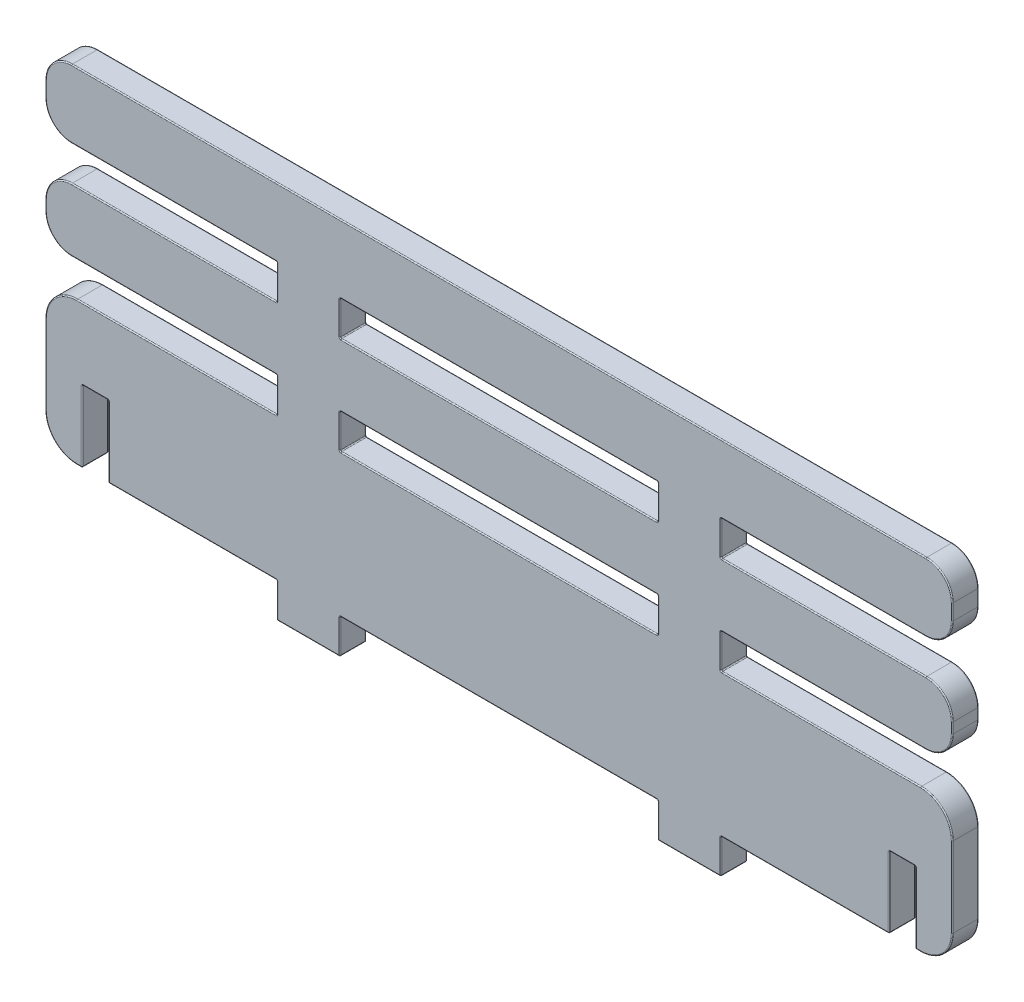
SolidWorks part; units mm, degrees
ref_plane "Plano frontal" through (0, 0, 0) normal (0, 0, 1) x (1, 0, 0)
ref_plane "Plano superior" through (0, 0, 0) normal (0, 1, 0) x (1, 0, 0)
ref_plane "Plano direito" through (0, 0, 0) normal (1, 0, 0) x (0, 0, -1)
sketch "Esboço1" plane through (0, 0, 0) normal (0, 0, 1) x (1, 0, 0)
  line L0 (-195.7976, 69.0191) -> (-116.5976, 69.0191)
  line L1 (-195.7976, 93.1191) -> (-195.7976, 86.3191)
  line L2 (-193.2976, 93.1191) -> (-193.2976, 86.3191)
  line L3 (-199.2976, 72.5188) -> (-199.2976, 119.0191) construction
  line L4 (-193.2976, 76.0191) -> (-195.7976, 76.0191)
  line L5 (-174.2976, 64.0191) -> (-174.2976, 119.0618) construction
  line L6 (-195.7976, 76.0191) -> (-195.7976, 83.0191)
  line L7 (-193.2976, 76.0191) -> (-193.2976, 83.0191)
  line L8 (-116.5976, 76.0191) -> (-116.5976, 83.0191)
  line L9 (-156.1976, 131.9283) -> (-156.1976, 54.9849) construction
  line L10 (-141.0976, 83.0191) -> (-141.0976, 112.5191) construction
  line L11 (-113.0976, 112.5191) -> (-199.2976, 112.5191)
  line L12 (-135.0976, 112.5191) -> (-135.0976, 83.0191) construction
  line L13 (-113.0976, 103.2191) -> (-199.2976, 103.2191)
  line L14 (-138.0976, 64.0191) -> (-138.0976, 119.0618) construction
  line L15 (-116.0976, 86.3191) -> (-196.2976, 86.3191)
  line L16 (-113.0976, 72.5188) -> (-113.0976, 119.0191) construction
  line L17 (-141.0976, 83.0191) -> (-141.0976, 86.3191)
  line L18 (-135.0976, 86.3191) -> (-141.0976, 86.3191)
  line L19 (-135.0976, 83.0191) -> (-135.0976, 86.3191)
  line L20 (-135.0976, 83.0191) -> (-141.0976, 83.0191)
  line L21 (-141.0976, 103.2191) -> (-141.0976, 99.9191)
  line L22 (-135.0976, 99.9191) -> (-141.0976, 99.9191)
  line L23 (-135.0976, 103.2191) -> (-135.0976, 99.9191)
  line L24 (-135.0976, 103.2191) -> (-141.0976, 103.2191)
  line L25 (-141.0976, 112.5191) -> (-141.0976, 109.2191)
  line L26 (-135.0976, 109.2191) -> (-141.0976, 109.2191)
  line L27 (-135.0976, 112.5191) -> (-135.0976, 109.2191)
  line L28 (-135.0976, 112.5191) -> (-141.0976, 112.5191)
  line L29 (-119.0976, 93.1191) -> (-116.5976, 93.1191)
  line L30 (-113.0976, 109.2191) -> (-113.0976, 103.2191)
  line L31 (-113.0976, 119.0191) -> (-113.0976, 112.5191)
  line L32 (-113.0976, 89.3191) -> (-113.0976, 96.9191)
  line L33 (-113.0976, 80.0191) -> (-113.0976, 72.5188)
  line L34 (-119.0976, 76.0191) -> (-119.0976, 83.0191)
  line L36 (-196.2976, 83.0191) -> (-116.0976, 83.0191)
  line L37 (-199.2976, 80.0191) -> (-199.2976, 72.5188)
  line L39 (-119.0976, 76.0191) -> (-116.5976, 76.0191)
  line L40 (-119.0976, 93.1191) -> (-119.0976, 86.3191)
  line L41 (-116.5976, 93.1191) -> (-116.5976, 86.3191)
  line L58 (-199.2976, 119.0191) -> (-113.0976, 119.0191)
  line L61 (-199.2976, 89.3191) -> (-199.2976, 96.9191)
  line L62 (-196.2976, 99.9191) -> (-116.0976, 99.9191)
  line L64 (-199.2976, 109.2191) -> (-113.0976, 109.2191)
  line L66 (-199.2976, 119.0191) -> (-199.2976, 112.5191)
  line L67 (-199.2976, 109.2191) -> (-199.2976, 103.2191)
  line L71 (-177.2976, 112.5191) -> (-177.2976, 83.0191) construction
  line L72 (-193.2976, 93.1191) -> (-195.7976, 93.1191)
  line L76 (-171.2976, 83.0191) -> (-171.2976, 112.5191) construction
  line L80 (-177.2976, 112.5191) -> (-171.2976, 112.5191)
  line L81 (-177.2976, 112.5191) -> (-177.2976, 109.2191)
  line L82 (-177.2976, 109.2191) -> (-171.2976, 109.2191)
  line L83 (-171.2976, 112.5191) -> (-171.2976, 109.2191)
  line L84 (-177.2976, 103.2191) -> (-171.2976, 103.2191)
  line L85 (-177.2976, 103.2191) -> (-177.2976, 99.9191)
  line L86 (-177.2976, 99.9191) -> (-171.2976, 99.9191)
  line L87 (-171.2976, 103.2191) -> (-171.2976, 99.9191)
  line L88 (-177.2976, 83.0191) -> (-171.2976, 83.0191)
  line L89 (-177.2976, 83.0191) -> (-177.2976, 86.3191)
  line L90 (-177.2976, 86.3191) -> (-171.2976, 86.3191)
  line L91 (-171.2976, 83.0191) -> (-171.2976, 86.3191)
  arc A0 (-116.0976, 86.3191) -> (-113.0976, 89.3191) centre (-116.0976, 89.3191) ccw
  arc A1 (-113.0976, 96.9191) -> (-116.0976, 99.9191) centre (-116.0976, 96.9191) ccw
  arc A2 (-116.0976, 83.0191) -> (-113.0976, 80.0191) centre (-116.0976, 80.0191) cw
  arc A3 (-116.5976, 69.0191) -> (-113.0976, 72.5188) centre (-116.5973, 72.5188) ccw
  arc A6 (-195.7976, 69.0191) -> (-199.2976, 72.5188) centre (-195.798, 72.5188) cw
  arc A7 (-196.2976, 83.0191) -> (-199.2976, 80.0191) centre (-196.2976, 80.0191) ccw
  arc A10 (-199.2976, 96.9191) -> (-196.2976, 99.9191) centre (-196.2976, 96.9191) cw
  arc A11 (-196.2976, 86.3191) -> (-199.2976, 89.3191) centre (-196.2976, 89.3191) cw
  point P8 (-156.1976, 83.0191)
  point P10 (-156.1976, 99.9191)
  point P11 (-156.1976, 112.5191)
  point P12 (-156.1976, 119.0191)
  point P13 (-156.1976, 103.2191)
  point P14 (-156.1976, 86.3191)
  point P48 (-156.1976, 109.2191)
  point P54 (-156.1976, 69.0191)
  dimension "D1" = 37.1
  dimension "D5" = 25
  dimension "D29" = 3
  dimension "D39" = 2.5
  dimension "D43" = 3
  dimension "D44" = 3
extrude "Ressalto-extrusão1" add sketch "Esboço1" along normal blind 2.5 contours L58 L66 L11 L31 | L64 L67 L13 L30 L26 | A11 L15 L1 L72 L2 L40 L29 L41 A0 L32 A1 L62 L22 A10 L61 | L83 L11 L81 L64 | L87 L13 L85 L62 | L36 L91 L15 L89 | L20 L19 L15 L17 | L23 L13 L21 L22 | L27 L11 L25 L26
fillet "Filete1" radius 2.5 8 edges at (-199.2976, 103.2191, 1.25) (-199.2976, 112.5191, 1.25) (-199.2976, 109.2191, 1.25) (-199.2976, 119.0191, 1.25) (-113.0976, 103.2191, 1.25) (-113.0976, 109.2191, 1.25) (-113.0976, 112.5191, 1.25) (-113.0976, 119.0191, 1.25)
fillet "Filete2" radius 0.1 128 edges at (-195.7976, 86.3191, 1.25) (-195.7976, 93.1191, 1.25) (-193.2976, 86.3191, 1.25) (-177.2976, 86.3191, 1.25) (-177.2976, 83.0191, 1.25) (-171.2976, 83.0191, 1.25) (-171.2976, 86.3191, 1.25) (-141.0976, 86.3191, 1.25) (-141.0976, 83.0191, 1.25) (-135.0976, 83.0191, 1.25) (-135.0976, 86.3191, 1.25) (-119.0976, 86.3191, 1.25) (-119.0976, 93.1191, 1.25) (-116.5976, 93.1191, 1.25) (-135.0976, 99.9191, 1.25) (-135.0976, 103.2191, 1.25) (-135.0976, 109.2191, 1.25) (-135.0976, 112.5191, 1.25) (-177.2976, 112.5191, 1.25) (-177.2976, 109.2191, 1.25) (-177.2976, 99.9191, 1.25) (-141.0976, 103.2191, 1.25) (-141.0976, 99.9191, 1.25) (-141.0976, 112.5191, 1.25) (-141.0976, 109.2191, 1.25) (-171.2976, 99.9191, 1.25) (-171.2976, 109.2191, 1.25) (-171.2976, 112.5191, 1.25) (-198.5654, 108.4869, 2.5) (-187.0476, 109.2191, 2.5) (-177.2976, 110.8691, 2.5) (-187.0476, 112.5191, 2.5) (-198.5654, 113.2514, 2.5) (-199.2976, 115.7691, 2.5) (-198.5654, 118.2869, 2.5) (-156.1976, 119.0191, 2.5) (-113.8299, 118.2869, 2.5) (-113.0976, 115.7691, 2.5) (-113.8299, 113.2514, 2.5) (-125.3476, 112.5191, 2.5) (-125.3476, 109.2191, 2.5) (-113.8299, 108.4869, 2.5) (-113.0976, 106.2191, 2.5) (-113.8299, 103.9514, 2.5) (-125.3476, 103.2191, 2.5) (-135.0976, 101.5691, 2.5) (-125.5976, 99.9191, 2.5) (-113.9763, 99.0405, 2.5) (-113.0976, 93.1191, 2.5) (-113.9763, 87.1978, 2.5) (-116.3476, 86.3191, 2.5) (-117.8476, 93.1191, 2.5) (-119.0976, 89.7191, 2.5) (-127.0976, 86.3191, 2.5) (-135.0976, 84.6691, 2.5) (-138.0976, 83.0191, 2.5) (-141.0976, 84.6691, 2.5) (-156.1976, 86.3191, 2.5) (-171.2976, 84.6691, 2.5) (-174.2976, 83.0191, 2.5) (-177.2976, 84.6691, 2.5) (-185.2976, 86.3191, 2.5) (-193.2976, 89.7191, 2.5) (-194.5476, 93.1191, 2.5) (-196.0476, 86.3191, 2.5) (-198.419, 87.1978, 2.5) (-198.419, 99.0405, 2.5) (-186.7976, 99.9191, 2.5) (-177.2976, 101.5691, 2.5) (-187.0476, 103.2191, 2.5) (-198.5654, 103.9514, 2.5) (-199.2976, 106.2191, 2.5) (-171.2976, 101.5691, 2.5) (-156.1976, 99.9191, 2.5) (-156.1976, 103.2191, 2.5) (-156.1976, 109.2191, 2.5) (-141.0976, 110.8691, 2.5) (-156.1976, 112.5191, 2.5) (-177.2976, 101.5691, 0) (-186.7976, 99.9191, 0) (-199.2976, 93.1191, 0) (-198.419, 87.1978, 0) (-196.0476, 86.3191, 0) (-195.7976, 89.7191, 0) (-194.5476, 93.1191, 0) (-193.2976, 89.7191, 0) (-185.2976, 86.3191, 0) (-177.2976, 84.6691, 0) (-174.2976, 83.0191, 0) (-171.2976, 84.6691, 0) (-156.1976, 86.3191, 0) (-141.0976, 84.6691, 0) (-138.0976, 83.0191, 0) (-135.0976, 84.6691, 0) (-127.0976, 86.3191, 0) (-117.8476, 93.1191, 0) (-116.5976, 89.7191, 0) (-116.3476, 86.3191, 0) (-113.9763, 87.1978, 0) (-113.0976, 93.1191, 0) (-113.9763, 99.0405, 0) (-125.5976, 99.9191, 0) (-135.0976, 101.5691, 0) (-113.8299, 103.9514, 0) (-113.0976, 106.2191, 0) (-113.8299, 108.4869, 0) (-125.3476, 109.2191, 0) (-135.0976, 110.8691, 0) (-125.3476, 112.5191, 0) (-113.8299, 113.2514, 0) (-113.0976, 115.7691, 0) (-113.8299, 118.2869, 0) (-156.1976, 119.0191, 0) (-199.2976, 115.7691, 0) (-198.5654, 113.2514, 0) (-177.2976, 110.8691, 0) (-187.0476, 109.2191, 0) (-198.5654, 108.4869, 0) (-198.5654, 103.9514, 0) (-187.0476, 103.2191, 0) (-141.0976, 101.5691, 0) (-156.1976, 99.9191, 0) (-171.2976, 101.5691, 0) (-156.1976, 103.2191, 0) (-141.0976, 110.8691, 0) (-156.1976, 109.2191, 0) (-171.2976, 110.8691, 0) (-156.1976, 112.5191, 0)
